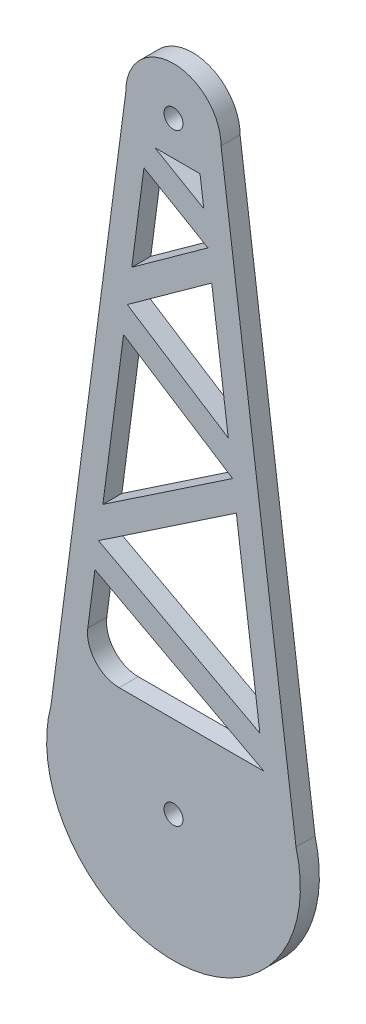
SolidWorks part; units mm, degrees
ref_plane "Front Plane" through (0, 0, 0) normal (0, 0, 1) x (1, 0, 0)
ref_plane "Top Plane" through (0, 0, 0) normal (0, 1, 0) x (1, 0, 0)
ref_plane "Right Plane" through (0, 0, 0) normal (1, 0, 0) x (0, 0, -1)
sketch "Sketch1" plane through (0, 0, 0) normal (0, 0, 1) x (1, 0, 0)
  line L0 (0, 0) -> (0, 168.6185) construction
  line L1 (-19.3193, 5.1736) -> (-7.5, 95)
  line L2 (19.3193, 5.1736) -> (7.5, 95)
  line L3 (-3.4653, 95.0019) -> (-16.4704, -3.8374) construction
  line L4 (3.4839, 94.8604) -> (16.4955, -4.0277) construction
  line L5 (-14.255, 13) -> (14.255, 13)
  line L6 (-14.255, 13) -> (-12.3856, 27.2077)
  line L7 (-2.8983, 89.5344) -> (4.1847, 89.5344)
  line L8 (4.1847, 89.5344) -> (4.7742, 85.0537)
  line L9 (-12.3856, 27.2077) -> (14.255, 13)
  line L10 (-11.8282, 31.4437) -> (13.6135, 17.8754)
  line L11 (-11.1322, 36.7332) -> (-7.8666, 61.5521)
  line L12 (-11.8282, 31.4437) -> (9.9042, 46.0664)
  line L13 (-11.1322, 36.7332) -> (9.3214, 50.4954)
  line L14 (9.9042, 46.0664) -> (13.6135, 17.8754)
  line L15 (9.3214, 50.4954) -> (-7.8666, 61.5521)
  line L16 (-7.2896, 65.9371) -> (8.6377, 55.6914)
  line L17 (-7.2896, 65.9371) -> (6.027, 75.5327)
  line L18 (-6.5729, 71.3838) -> (5.4345, 80.036)
  line L19 (5.4345, 80.036) -> (-4.6589, 85.9304)
  line L20 (4.7742, 85.0537) -> (-2.8983, 89.5344)
  line L21 (-6.5729, 71.3838) -> (-4.6589, 85.9304)
  line L22 (6.027, 75.5327) -> (8.6377, 55.6914)
  arc A0 (-19.3193, 5.1736) -> (19.3193, 5.1736) centre (0, 0) ccw
  arc A1 (7.5, 95) -> (-7.5, 95) centre (0, 95) ccw
  circle A2 centre (0, 95) radius 1.5
  circle A3 centre (0, 0) radius 1.5
  dimension "D1" = 40
  dimension "D2" = 15
  dimension "D3" = 3
  dimension "D4" = 3
  dimension "D5" = 95
  dimension "D6" = 4
  dimension "D7" = 4
  dimension "D8" = 4
  dimension "D9" = 13
  dimension "D10" = 4
  dimension "D11" = 4
  dimension "D12" = 4
  dimension "D13" = 4
extrude "Boss-Extrude1" add sketch "Sketch1" along normal blind 3
fillet "Fillet1" radius 5 1 edges at (-14.255, 13, 1.5)
